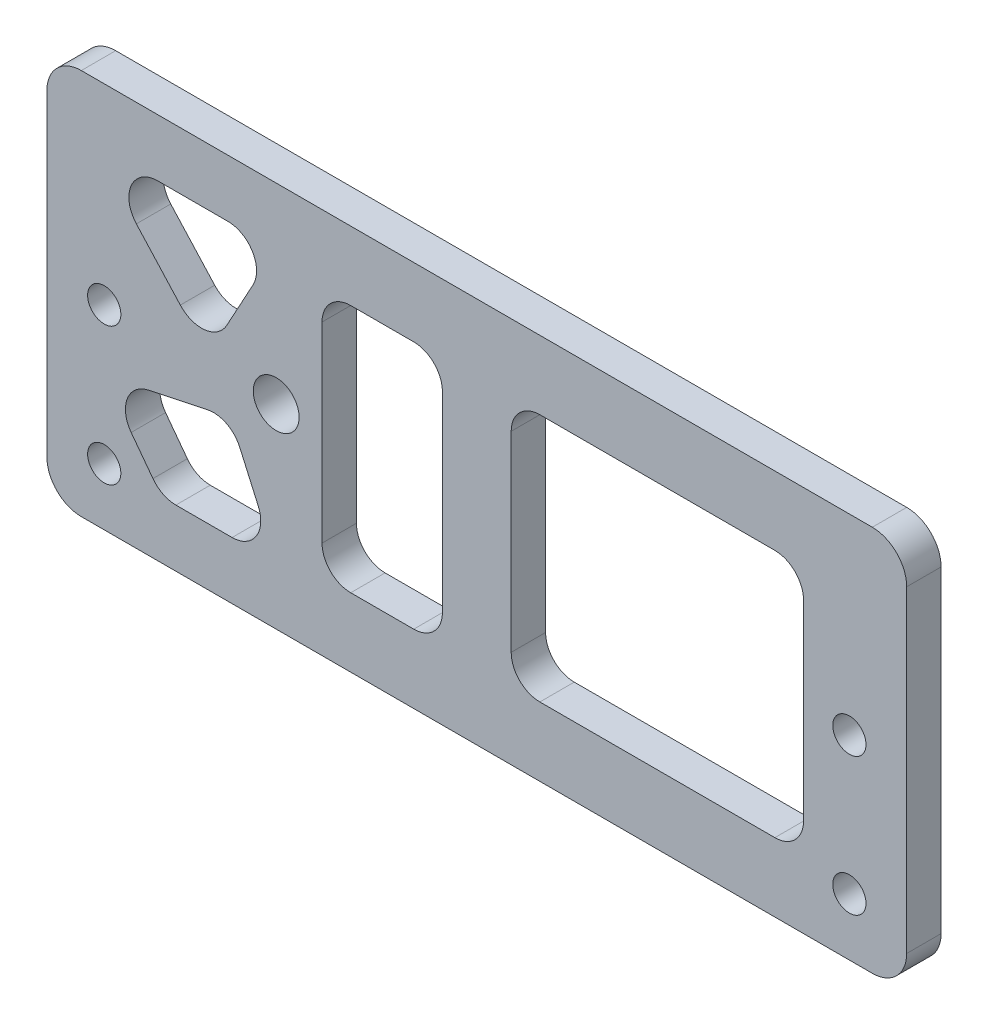
SolidWorks part; units mm, degrees
material "Thornel Mat VMA"
ref_plane "前视基准面" through (0, 0, 0) normal (0, 0, 1) x (1, 0, 0)
ref_plane "上视基准面" through (0, 0, 0) normal (0, 1, 0) x (1, 0, 0)
ref_plane "右视基准面" through (0, 0, 0) normal (1, 0, 0) x (0, 0, -1)
sketch "草图1" plane through (0, 0, 0) normal (0, 0, 1) x (1, 0, 0)
  line L1 (0, 0) -> (75, 0)
  line L2 (0, 0) -> (0, 33.7)
  line L3 (0, 33.7) -> (75, 33.7)
  line L4 (75, 0) -> (75, 33.7)
  circle A0 centre (5, 17) radius 1.45
  circle A1 centre (5, 5) radius 1.45
  circle A2 centre (70, 17) radius 1.45
  circle A3 centre (70, 5) radius 1.45
  circle A4 centre (20, 17) radius 2
  dimension "D1" = 2.9
  dimension "D2" = 2.9
  dimension "D3" = 2.9
  dimension "D4" = 2.9
  dimension "D5" = 12
  dimension "D6" = 5
  dimension "D7" = 5
  dimension "D8" = 5
  dimension "D9" = 5
  dimension "D10" = 5
  dimension "D11" = 5
  dimension "D12" = 12
  dimension "D13" = 65
  dimension "D15" = 4
  dimension "D16" = 17
  dimension "D17" = 20
  dimension "D14" = 33.7
extrude "凸台-拉伸1" add sketch "草图1" along normal blind 3
sketch "草图2" plane through (0, 0, 3) normal (0, 0, 1) x (1, 0, 0)
  line L6 (4, 28.7) -> (20, 28.7)
  line L7 (40.5, 27.7) -> (66, 27.7)
  line L8 (40.5, 27.7) -> (40.5, 6)
  line L9 (40.5, 6) -> (66, 6)
  line L10 (66, 27.7) -> (66, 6)
  line L11 (24, 27.7) -> (34.5, 27.7)
  line L12 (24, 27.7) -> (24, 6)
  line L13 (24, 6) -> (34.5, 6)
  line L14 (34.5, 27.7) -> (34.5, 6)
  line L15 (20, 28.7) -> (14, 17.7)
  line L16 (14, 17.7) -> (4, 28.7)
  line L17 (5, 11.6667) -> (16, 14)
  line L18 (16, 14) -> (20, 5)
  line L19 (20, 5) -> (10, 5)
  line L20 (10, 5) -> (5, 11.6667)
  line L21 (37.5, 33.7) -> (37.5, 0) construction
  line L22 (75, 33.7) -> (0, 33.7) construction
  line L23 (0, 0) -> (75, 0) construction
  line L24 (0, 33.7) -> (0, 0) construction
  circle A0 centre (20, 17) radius 2 construction
  circle A1 centre (5, 5) radius 1.45 construction
  circle A2 centre (70, 17) radius 1.45 construction
  dimension "D3" = 4
  dimension "D1" = 3
  dimension "D2" = 3
  dimension "D4" = 6
  dimension "D5" = 6
  dimension "D6" = 6
  dimension "D7" = 6
  dimension "D8" = 5
  dimension "D9" = 4
  dimension "D10" = 5
  dimension "D11" = 4
  dimension "D12" = 4
  dimension "D13" = 16
  dimension "D14" = 14
  dimension "D15" = 20
  dimension "D16" = 10
  dimension "D17" = 5
  dimension "D18" = 14
  dimension "D19" = 16
  dimension "D20" = 20
extrude "切除-拉伸1" cut sketch "草图2" against normal blind 10
fillet "圆角1" radius 2.5 15 edges at (24, 27.7, 1.5) (34.5, 27.7, 1.5) (34.5, 6, 1.5) (24, 6, 1.5) (4, 28.7, 1.5) (20, 28.7, 1.5) (5, 11.6667, 1.5) (16, 14, 1.5) (20, 5, 1.5) (10, 5, 1.5) (40.5, 27.7, 1.5) (66, 27.7, 1.5) (66, 6, 1.5) (40.5, 6, 1.5) (14, 17.7, 1.5)
fillet "圆角2" radius 3 4 edges at (75, 33.7, 1.5) (75, 0, 1.5) (0, 0, 1.5) (0, 33.7, 1.5)
